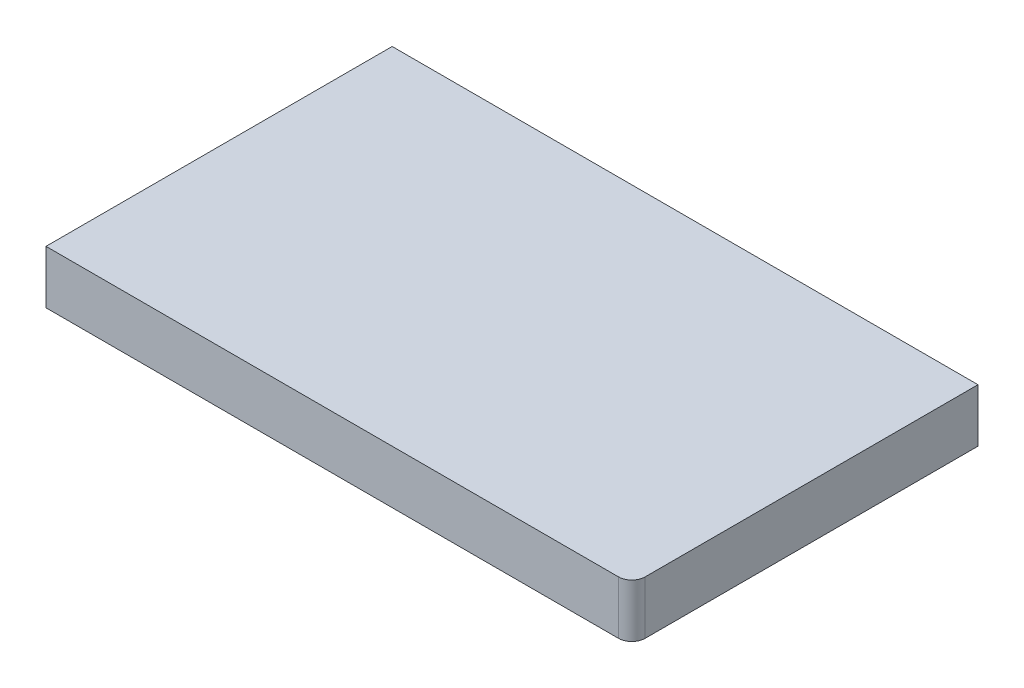
SolidWorks part; units mm, degrees
ref_plane "Front Plane" through (0, 0, 0) normal (0, 0, 1) x (1, 0, 0)
ref_plane "Top Plane" through (0, 0, 0) normal (0, 1, 0) x (1, 0, 0)
ref_plane "Right Plane" through (0, 0, 0) normal (1, 0, 0) x (0, 0, -1)
sketch "Sketch1" plane through (0, 0, 0) normal (0, 1, 0) x (1, 0, 0)
  line L1 (-11, -6.5) -> (11, -6.5)
  line L2 (-11, -6.5) -> (-11, 6.5)
  line L3 (-11, 6.5) -> (11, 6.5)
  line L4 (11, -6.5) -> (11, 6.5)
  line L5 (-11, -6.5) -> (11, 6.5) construction
  line L6 (-11, 6.5) -> (11, -6.5) construction
  point P0 (0, 0)
  dimension "D1" = 13
  dimension "D2" = 22
extrude "Boss-Extrude1" add sketch "Sketch1" along normal mid plane 2
fillet "Fillet1" radius 0.5 1 edges at (11, 0, 6.5)
